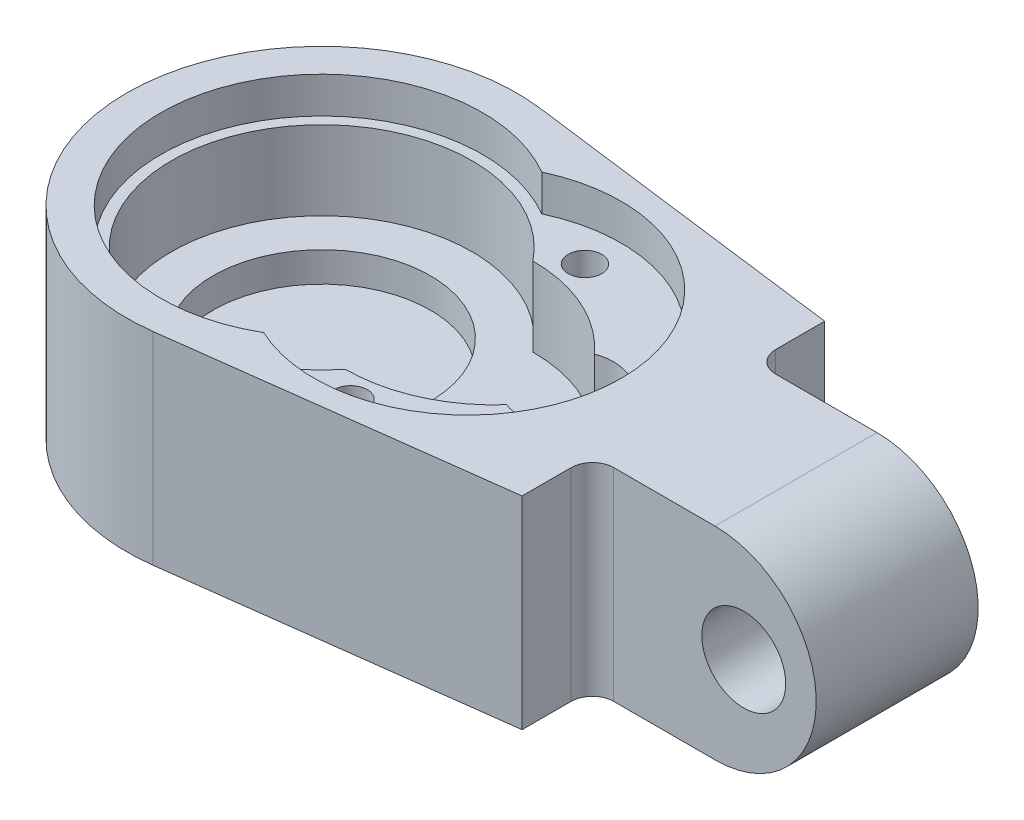
SolidWorks part; units mm, degrees
material "AISI Type A2 Tool Steel"
ref_plane "Front" through (0, 0, 0) normal (0, 0, 1) x (1, 0, 0)
ref_plane "Top" through (0, 0, 0) normal (0, 1, 0) x (1, 0, 0)
ref_plane "Right" through (0, 0, 0) normal (1, 0, 0) x (0, 0, -1)
sketch "Sketch1" plane through (0, 0, 0) normal (0, 1, 0) x (1, 0, 0)
  line L0 (0, 0) -> (20.955, 0) construction
  line L1 (20.955, 9.017) -> (20.955, 4.826)
  line L2 (1.4847, 11.5253) -> (20.955, 9.017)
  line L3 (1.4847, -11.5253) -> (20.955, -9.017)
  line L4 (20.955, 0) -> (34.29, 0) construction
  line L5 (34.29, 4.826) -> (34.29, -4.826)
  line L6 (34.29, 4.826) -> (20.955, 4.826)
  line L7 (34.29, -4.826) -> (20.955, -4.826)
  line L8 (20.955, -4.826) -> (20.955, -9.017)
  arc A0 (1.4847, 11.5253) -> (1.4847, -11.5253) centre (0, 0) ccw
  dimension "D1" = 23.241
  dimension "D2" = 20.955
  dimension "D3" = 18.034
  dimension "D4" = 13.335
  dimension "D5" = 9.652
  dimension "D6" = 14.681
extrude "Boss-Extrude1" add sketch "Sketch1" along normal blind 12.065
fillet "Fillet2" radius 1.27 1 edges at (20.955, 6.0325, 4.826)
fillet "Fillet3" radius 1.27 1 edges at (20.955, 6.0325, -4.826)
sketch "Sketch3" plane through (0, 0, -4.826) normal (0, 0, -1) x (-1, 0, 0)
  line L0 (-34.29, 6.0325) -> (-22.225, 6.0325) construction
  line L1 (-34.29, 12.065) -> (-34.29, 0) construction
  line L2 (-28.2575, 12.065) -> (-34.29, 12.065)
  line L3 (-34.29, 12.065) -> (-34.29, 0)
  line L4 (-34.29, 0) -> (-28.2575, 0)
  arc A0 (-28.2575, 12.065) -> (-28.2575, 0) centre (-28.2575, 6.0325) ccw
  line M5 (-34.29, 0) -> (-22.225, 0)
  line M7 (-22.225, 12.065) -> (-34.29, 12.065)
  line M8 (-34.29, 12.065) -> (-34.29, 0)
  dimension "D1" = 12.065
  dimension "D2" = 6.0325
extrude "Cut-Extrude1" cut sketch "Sketch3" against normal up to next contours A0 M7 M8 | A0 L3 M5
hole_wizard "Ø5.0 (5) Diameter Hole1" positions "Sketch17" profile "Sketch18" hole size "Ø5.0" standard "ANSI Metric" end condition through all
sketch "Sketch17" plane through (0, 0, 4.826) normal (0, 0, 1) x (1, 0, 0)
  line L0 (34.29, 6.0325) -> (29.972, 6.0325) construction
  arc A0 (28.2575, 0) -> (28.2575, 12.065) centre (28.2575, 6.0325) ccw construction
  point P0 (29.972, 6.0325)
  point P10 (29.972, 6.0325)
  dimension "D1" = 4.318
sketch "Sketch18" plane through (29.972, 6.0325, 4.826) normal (1, 0, 0) x (0, -1, 0)
  line L0 (0, 0) -> (0, 16.4465)
  line L1 (0, 16.4465) -> (2.5, 16.4465)
  line L2 (2.5, 16.4465) -> (2.5, 0)
  line L5 (2.5, 0) -> (0, 0)
  line L11 (0, -6.35) -> (0, 107.95) construction
  dimension "Thru Hole Dia." = 5
  dimension "Thru Hole Depth" = 16.4465
sketch "Sketch8" plane through (0, 12.065, 0) normal (0, 1, 0) x (1, 0, 0)
  line L0 (-9.5885, 0) -> (17.8435, 0) construction
  line L1 (8.6995, 0) -> (17.8435, 0) construction
  arc A0 (4.8283, 8.2841) -> (4.8283, -8.2841) centre (0, 0) ccw
  arc A2 (4.8283, -8.2841) -> (4.8283, 8.2841) centre (8.6995, 0) ccw
  dimension "D1" = 19.177
  dimension "D3" = 18.288
  dimension "D2" = 27.432
extrude "Cut-Extrude2" cut sketch "Sketch8" against normal blind 2.159
sketch "Sketch9" plane through (0, 9.906, 0) normal (0, 1, 0) x (1, 0, 0)
  line L0 (6.9957, 5.588) -> (6.9957, -5.588) construction
  line L1 (34.29, 0) -> (15.24, 0) construction
  line L2 (34.29, -4.826) -> (34.29, 4.826) construction
  line L3 (6.9957, 0) -> (15.24, 0) construction
  arc A0 (6.9957, 5.588) -> (6.9957, -5.588) centre (0, 0) ccw
  arc A1 (6.9957, 5.588) -> (15.24, 0) centre (6.9957, -3.2877) cw
  arc A2 (6.9957, -5.588) -> (15.24, 0) centre (6.9957, 3.2877) ccw
  dimension "D1" = 17.907
  dimension "D2" = 11.176
  dimension "D3" = 19.05
extrude "Cut-Extrude3" cut sketch "Sketch9" against normal blind 4.699
hole_wizard "#97 (0.22) Diameter Hole1" positions "Sketch10" profile "Sketch11" hole size "#97" standard "ANSI Inch" end condition through all
sketch "Sketch10" plane through (0, 0, 0) normal (0, -1, 0) x (-1, 0, 0)
  line L0 (-34.29, 0) -> (-14.605, 0) construction
  line L1 (-34.29, 4.826) -> (-34.29, -4.826) construction
  point P0 (-14.605, 0)
  dimension "D1" = 19.685
sketch "Sketch11" plane through (14.605, 0, 0) normal (1, 0, 0) x (0, 0, -1)
  line L0 (0, 0) -> (0, 12.065)
  line L1 (0, 12.065) -> (2.794, 12.065)
  line L2 (2.794, 12.065) -> (2.794, 0)
  line L5 (2.794, 0) -> (0, 0)
  line L11 (0, -6.35) -> (0, 107.95) construction
  dimension "Thru Hole Dia." = 5.588
  dimension "Thru Hole Depth" = 12.065
sketch "Sketch12" plane through (0, 5.207, 0) normal (0, 1, 0) x (1, 0, 0)
  circle A0 centre (0, 0) radius 6.477
  dimension "D1" = 12.954
extrude "Cut-Extrude4" cut sketch "Sketch12" against normal blind 1.778
hole_wizard "M2x0.4 Tapped Hole1" positions "Sketch15" profile "Sketch16" tap size "M2x0.4" standard "ANSI Metric"
sketch "Sketch15" plane through (0, 9.906, 0) normal (0, 1, 0) x (1, 0, 0)
  line L0 (17.8435, 0) -> (8.6995, 0) construction
  line L2 (8.6995, 6.985) -> (8.6995, -6.985) construction
  arc A0 (4.8283, -8.2841) -> (4.8283, 8.2841) centre (8.6995, 0) ccw construction
  point P0 (8.6995, 6.985)
  point P2 (8.6995, -6.985)
  point P17 (8.6995, 0)
  dimension "D1" = 9.144
  dimension "D2" = 13.97
sketch "Sketch16" plane through (8.6995, 9.906, -6.985) normal (1, 0, 0) x (0, 0, 1)
  line L0 (0, 0) -> (0, 4.8427)
  line L1 (0, 4.8427) -> (1, 4.2418)
  line L2 (1, 4.2418) -> (1, 0)
  line L5 (1, 0) -> (0, 0)
  line L10 (0, 4.8427) -> (-1, 4.2418) construction
  line L11 (0, -6.35) -> (0, 107.95) construction
  dimension "Tap Drill Dia." = 2
  dimension "Tap Drill Depth" = 4.2418
  dimension "Drill Angle" = 118
cosmetic thread "Hole Thread1" parameters "D1"=3.048, "D2"=2
cosmetic thread "Hole Thread2" parameters "D1"=3.048, "D2"=2
